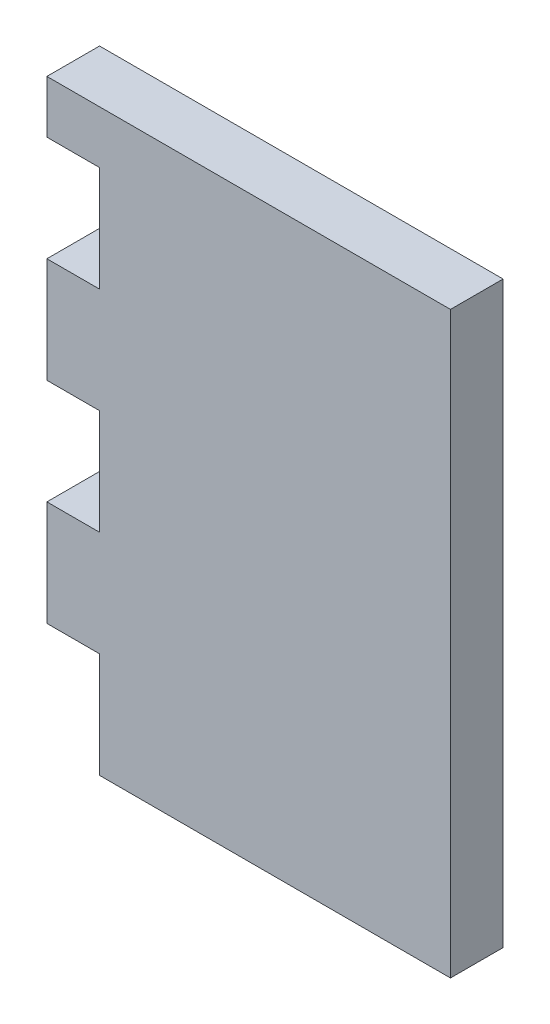
SolidWorks part; units mm, degrees
material "Pine"
ref_plane "Front Plane" through (0, 0, 0) normal (0, 0, 1) x (1, 0, 0)
ref_plane "Top Plane" through (0, 0, 0) normal (0, 1, 0) x (1, 0, 0)
ref_plane "Right Plane" through (0, 0, 0) normal (1, 0, 0) x (0, 0, -1)
sketch "Sketch1" plane through (0, 0, 0) normal (0, 0, 1) x (1, 0, 0)
  line L0 (0, -42) -> (0, -30)
  line L5 (0, 0) -> (46, 0)
  line L6 (0, 0) -> (0, -66)
  line L7 (0, -66) -> (46, -66)
  line L8 (46, 0) -> (46, -66)
  line L9 (0, -66) -> (6, -66)
  line L10 (0, -66) -> (0, -54)
  line L11 (0, -54) -> (6, -54)
  line L12 (6, -66) -> (6, -54)
  line L13 (0, -42) -> (6, -42)
  line L14 (6, -42) -> (6, -30)
  line L15 (0, -30) -> (6, -30)
  line L16 (0, -18) -> (0, -6)
  line L17 (0, -18) -> (6, -18)
  line L18 (6, -18) -> (6, -6)
  line L19 (0, -6) -> (6, -6)
  dimension "D1" = 66
  dimension "D2" = 46
  dimension "D3" = 6
  dimension "D4" = 12
  dimension "D5" = 3
extrude "Boss-Extrude1" add sketch "Sketch1" along normal blind 6 contours L6 L19 L18 L17 L15 L14 L13 L11 L12 L7 L8 L5
